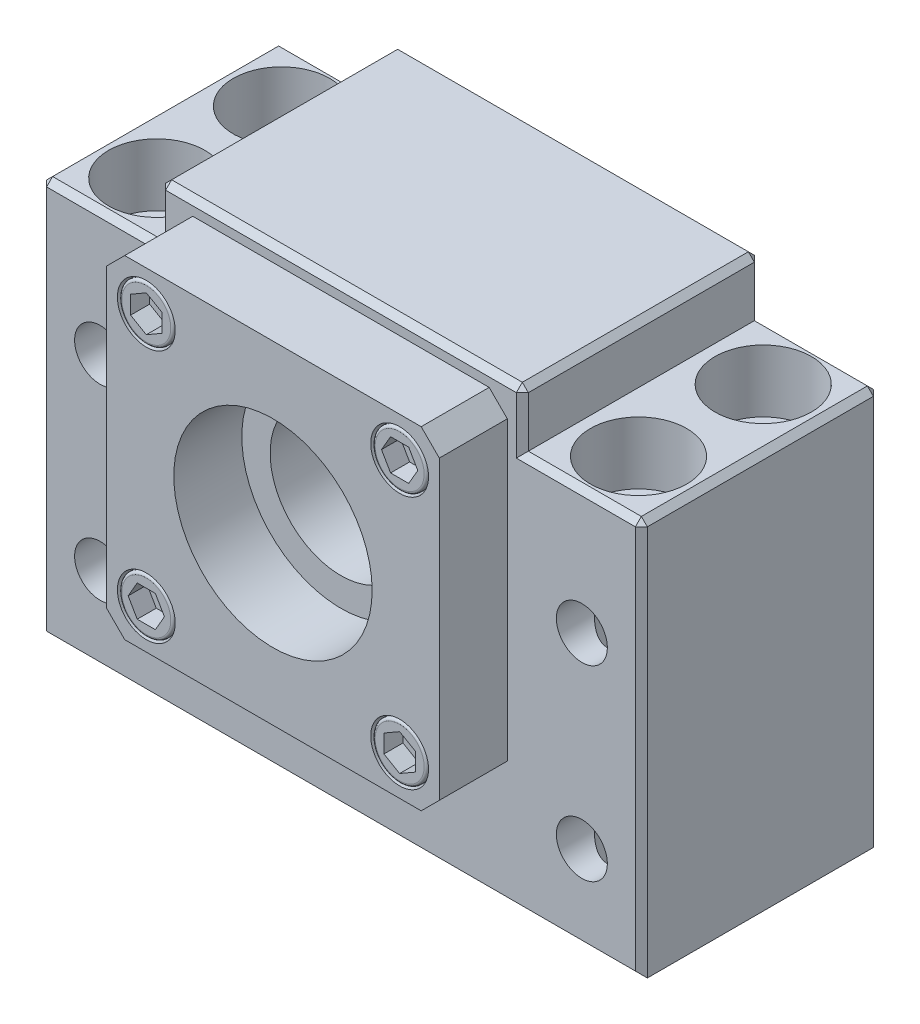
SolidWorks part; units mm, degrees
ref_plane "前视基准面" through (0, 0, 0) normal (0, 0, 1) x (1, 0, 0)
ref_plane "上视基准面" through (0, 0, 0) normal (0, 1, 0) x (1, 0, 0)
ref_plane "右视基准面" through (0, 0, 0) normal (1, 0, 0) x (0, 0, -1)
sketch "草图1" plane through (0, 0, 0) normal (0, 0, 1) x (1, 0, 0)
  line L0 (-53, 0) -> (53, 0)
  line L1 (53, 0) -> (53, 70)
  line L2 (53, 70) -> (32, 70)
  line L3 (32, 70) -> (32, 80)
  line L4 (32, 80) -> (-32, 80)
  line L5 (0, 80) -> (0, 0) construction
  line L6 (-32, 80) -> (-32, 70)
  line L7 (-32, 70) -> (-53, 70)
  line L8 (-53, 70) -> (-53, 0)
  line L9 (-42.5, 70) -> (-42.5, 0) construction
  line L10 (42.5, 70) -> (42.5, 0) construction
  line L11 (-51, 70) -> (-51, 59)
  line L12 (-51, 59) -> (-48, 59)
  line L13 (-48, 59) -> (-48, 0)
  line L14 (0, 48) -> (29.35, 77.35) construction
  line L15 (-29.35, 77.35) -> (29.35, 77.35)
  line L16 (-29.35, 77.35) -> (-29.35, 18.65)
  line L17 (-29.35, 18.65) -> (29.35, 18.65)
  line L18 (29.35, 77.35) -> (29.35, 18.65)
  line L19 (22.35, 70.35) -> (23.95, 70.35) construction
  line L20 (23.95, 73.1213) -> (20.75, 73.1213)
  line L21 (20.75, 73.1213) -> (19.15, 70.35)
  line L22 (19.15, 70.35) -> (20.75, 67.5787)
  line L23 (20.75, 67.5787) -> (23.95, 67.5787)
  line L24 (23.95, 67.5787) -> (25.55, 70.35)
  line L25 (25.55, 70.35) -> (23.95, 73.1213)
  line L26 (23.95, 70.35) -> (25.55, 70.35) construction
  line L27 (25.55, 70.35) -> (27.15, 70.35) construction
  line L28 (25.55, 70.35) -> (29.35, 70.35)
  circle A0 centre (0, 48) radius 12.5
  circle A1 centre (22.35, 70.35) radius 2.7713
  circle A2 centre (0, 48) radius 17.5
  circle A3 centre (22.35, 70.35) radius 5.1
  circle A4 centre (22.35, 70.35) radius 4.8
  circle A5 centre (-42.5, 48) radius 4.5
  circle A6 centre (-42.5, 15) radius 4.5
  circle A7 centre (22.35, 70.35) radius 2.7713 construction
  point P25 (0, 77.35)
  point P45 (27.45, 70.35)
  dimension "d1" = 25
  dimension "D4" = 9.6
  dimension "T" = 35
  dimension "D5" = 0.3
  dimension "d2" = 9
  dimension "(b)" = 53
  dimension "B" = 106
  dimension "H" = 80
  dimension "(h)" = 48
  dimension "B1" = 64
  dimension "H1" = 70
  dimension "P" = 85
  dimension "X" = 11
  dimension "Y" = 17
  dimension "Z" = 11
  dimension "D3" = 2.65
  dimension "E" = 33
  dimension "D7" = 2.65
sketch "草图2" plane through (0, 0, 0) normal (1, 0, 0) x (0, 0, -1)
  line L0 (21, 0) -> (-21, 0)
  line L1 (-21, 0) -> (-33, 0)
  point P3 (0, 0)
  point P5 (11, 0)
  point P8 (-11, 0)
  dimension "L" = 42
  dimension "L1" = 12
  dimension "C2" = 10
  dimension "C1" = 22
sketch "草图3" plane through (0, 0, 0) normal (0, 0, 1) x (1, 0, 0)
  line L0 (-53, 70) -> (-53, 0) construction
  line L1 (-53, 0) -> (53, 0) construction
  line L2 (53, 0) -> (53, 70) construction
  line L3 (53, 70) -> (32, 70) construction
  line L4 (32, 70) -> (32, 80) construction
  line L5 (32, 80) -> (-32, 80) construction
  line L6 (-32, 80) -> (-32, 70) construction
  line L7 (-32, 70) -> (-53, 70) construction
  line L8 (-53, 70) -> (-53, 0)
  line L9 (-53, 0) -> (53, 0)
  line L10 (53, 0) -> (53, 70)
  line L11 (53, 70) -> (32, 70)
  line L12 (32, 70) -> (32, 80)
  line L13 (32, 80) -> (-32, 80)
  line L14 (-32, 80) -> (-32, 70)
  line L15 (-32, 70) -> (-53, 70)
extrude "凸台-拉伸1" add sketch "草图3" along normal up to vertex (21 mm away) and the other way up to vertex (21 mm away) up to point (0, 0, 21) other way up to point (0, 0, -21)
chamfer "倒角1" distance 1.06 angle 45 20 edges at (-53, 35, -21) (0, 0, -21) (53, 35, -21) (42.5, 70, -21) (32, 75, -21) (0, 80, -21) (-32, 75, -21) (-42.5, 70, -21) (-32, 75, 21) (-32, 80, 0) (0, 80, 21) (32, 80, 0) (32, 75, 21) (42.5, 70, 21) (-42.5, 70, 21) (-53, 70, 0) (-53, 35, 21) (0, 0, 21) (53, 35, 21) (53, 70, 0)
sketch "草图10" plane through (0, 70, 0) normal (0, 1, 0) x (1, 0, 0)
  circle A0 centre (-42.5, -11) radius 8.5 construction
  circle A1 centre (-42.5, 11) radius 8.5 construction
  circle A2 centre (-42.5, 11) radius 5.5
  circle A3 centre (-42.5, -11) radius 5.5
  point P4 (-51, -11)
  point P10 (-48, -11)
extrude "切除-拉伸4" cut sketch "草图10" against normal up to vertex (70 mm away) up to point (-53, 0, 0)
sketch "草图11" plane through (0, 70, 0) normal (0, 1, 0) x (1, 0, 0)
  circle A0 centre (-42.5, 11) radius 8.5 construction
  circle A1 centre (-42.5, -11) radius 8.5 construction
  circle A2 centre (-42.5, 11) radius 8.5
  circle A3 centre (-42.5, -11) radius 8.5
extrude "切除-拉伸5" cut sketch "草图11" against normal up to vertex (11 mm away) up to point (-48, 59, 0)
sketch "草图13" plane through (0, 0, 21) normal (0, 0, 1) x (1, 0, 0)
  circle A0 centre (-42.5, 48) radius 4.5 construction
  circle A1 centre (-42.5, 15) radius 4.5 construction
  circle A2 centre (-42.5, 48) radius 4.5
  circle A3 centre (-42.5, 15) radius 4.5
extrude "切除-拉伸7" cut sketch "草图13" against normal through all
mirror "镜向1" about plane through (0, 0, 0) normal (1, 0, 0) of "切除-拉伸7", "切除-拉伸4", "切除-拉伸5"
sketch "草图6" plane through (0, 0, 0) normal (0, 0, 1) x (1, 0, 0)
  line L0 (-29.35, 77.35) -> (-29.35, 18.65) construction
  line L1 (-29.35, 18.65) -> (29.35, 18.65) construction
  line L2 (29.35, 77.35) -> (29.35, 18.65) construction
  line L3 (-29.35, 77.35) -> (29.35, 77.35) construction
  line L4 (-29.35, 77.35) -> (-29.35, 18.65)
  line L5 (-29.35, 18.65) -> (29.35, 18.65)
  line L6 (29.35, 77.35) -> (29.35, 18.65)
  line L7 (-29.35, 77.35) -> (29.35, 77.35)
extrude "凸台-拉伸2" add sketch "草图6" along normal up to vertex (33 mm away) up to point (0, 0, 33)
chamfer "倒角2" distance 3.2 angle 45 4 edges at (29.35, 77.35, 27) (29.35, 18.65, 27) (-29.35, 18.65, 27) (-29.35, 77.35, 27)
sketch "草图7" plane through (0, 0, 33) normal (0, 0, 1) x (1, 0, 0)
  circle A2 centre (22.35, 70.35) radius 5.1 construction
  circle A3 centre (22.35, 70.35) radius 4.8 construction
  circle A4 centre (22.35, 70.35) radius 4.8
  circle A5 centre (22.35, 70.35) radius 5.1
extrude "切除-拉伸1" cut sketch "草图7" against normal blind 5.76
sketch "草图12" plane through (0, 0, 33) normal (0, 0, 1) x (1, 0, 0)
  line L0 (25.55, 70.35) -> (23.95, 73.1213) construction
  line L1 (23.95, 73.1213) -> (20.75, 73.1213) construction
  line L2 (20.75, 73.1213) -> (19.15, 70.35) construction
  line L3 (19.15, 70.35) -> (20.75, 67.5787) construction
  line L4 (20.75, 67.5787) -> (23.95, 67.5787) construction
  line L5 (23.95, 67.5787) -> (25.55, 70.35) construction
  line L6 (25.55, 70.35) -> (23.95, 73.1213)
  line L7 (23.95, 73.1213) -> (20.75, 73.1213)
  line L24 (20.75, 73.1213) -> (19.15, 70.35)
  line L25 (19.15, 70.35) -> (20.75, 67.5787)
  line L26 (20.75, 67.5787) -> (23.95, 67.5787)
  line L27 (23.95, 67.5787) -> (25.55, 70.35)
extrude "切除-拉伸6" cut sketch "草图12" against normal blind 3.36
sketch "草图8" plane through (0, 0, 33) normal (0, 0, 1) x (1, 0, 0)
  circle A0 centre (0, 48) radius 17.5 construction
  circle A1 centre (0, 48) radius 17.5
extrude "切除-拉伸2" cut sketch "草图8" against normal up to vertex (12 mm away) up to point (0, 0, 21)
sketch "草图9" plane through (0, 0, 21) normal (0, 0, 1) x (1, 0, 0)
  circle A0 centre (0, 48) radius 12.5 construction
  circle A1 centre (0, 48) radius 12.5
extrude "切除-拉伸3" cut sketch "草图9" against normal up to vertex (42 mm away) up to point (0, 0, -21)
fillet "圆角1" radius 0.48 1 edges at (27.15, 70.35, 33)
pattern_circular "阵列(圆周)3" count 4 over 360 about axis through (0, 48, 0) along (0, 0, 1) of "切除-拉伸1", "切除-拉伸6", "圆角1"
